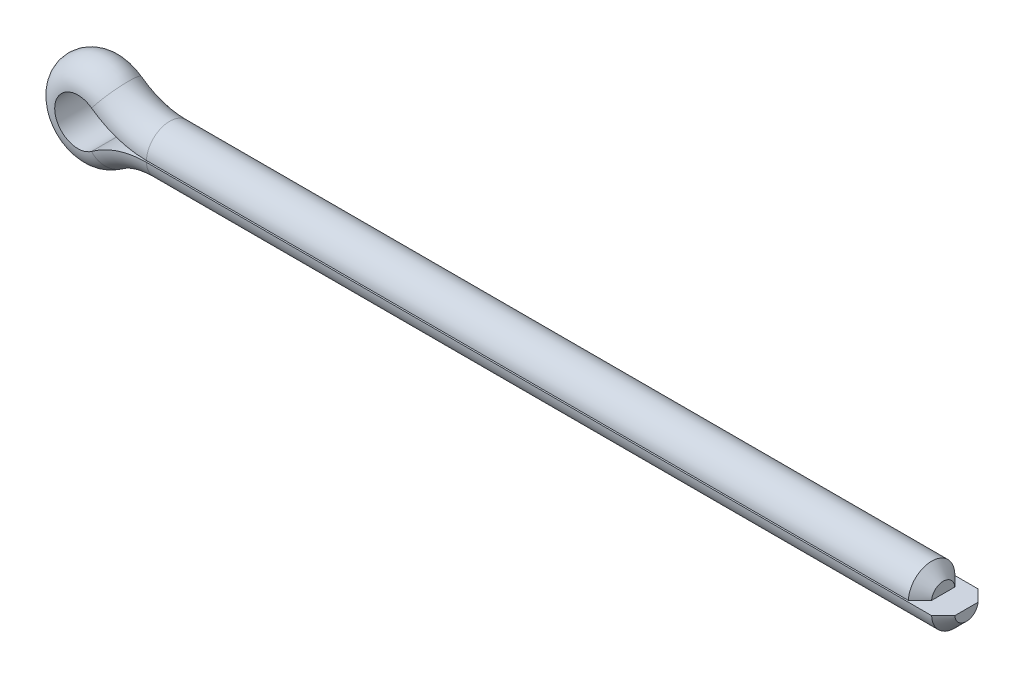
SolidWorks part; units mm, degrees
material "AISI 1020 Steel, Cold Rolled"
ref_plane "Front" through (0, 0, 0) normal (0, 0, 1) x (1, 0, 0)
ref_plane "Top" through (0, 0, 0) normal (0, 1, 0) x (1, 0, 0)
ref_plane "Right" through (0, 0, 0) normal (1, 0, 0) x (0, 0, -1)
sketch "Sketch1" plane through (0, 0, 0) normal (0, 0, 1) x (1, 0, 0)
  line L0 (-27.6517, 0) -> (0.762, 0) construction
  line L1 (-25.4, -0.0254) -> (0.762, -0.0254)
  line L2 (-26.8902, 0.0254) -> (0.762, 0.0254) construction
  line L3 (-25.4, 0.0254) -> (0, 0.0254)
  line L4 (-11.4985, 0.0254) -> (0.762, 0.0254) construction
  line L5 (-11.4985, -0.0254) -> (0.762, -0.0254) construction
  line L6 (-27.6517, 0.762) -> (-27.6517, 0) construction
  line L7 (-27.6517, 0.762) -> (-27.6517, 1.524) construction
  line L8 (-11.4985, 0) -> (0.762, 0) construction
  line L9 (0, 0.0254) -> (0, 0) construction
  line L10 (-27.6517, 0) -> (-27.6517, -1.524) construction
  line L11 (-25.4, 0.7366) -> (-25.4, -0.7874) construction
  arc A1 (-27.2014, 0.6147) -> (-27.2014, -0.6147) centre (-27.6517, 0) ccw
  arc A2 (-25.4, -0.0254) -> (-27.2014, -0.6147) centre (-25.4, -3.0734) ccw
  arc A3 (-27.2014, 0.6147) -> (-25.4, 0.0254) centre (-25.4, 3.0734) ccw
  circle A4 centre (-27.6517, 0) radius 1.524 construction
  point P15 (0, 0.0254)
  dimension "D6" = 3.048
  dimension "Head Diameter" = 3.048
  dimension "ExtendedProngLength" = 0.762
  dimension "Length" = 25.4
  dimension "Diameter" = 1.524
  dimension "D1" = 0.762
  dimension "D4" = 0.0254
  dimension "D5" = 0.0254
sketch "Sketch2" plane through (0, 0, 0) normal (1, 0, 0) x (0, 0, -1)
  line L0 (-0.7616, 0.0254) -> (0.7616, 0.0254)
  line L1 (0, 0.762) -> (0, -0.762) construction
  circle A1 centre (0, 0) radius 0.762 construction
  arc A2 (-0.7616, 0.0254) -> (0.7616, 0.0254) centre (0, 0) cw
  point P5 (0, 0)
  dimension "D1" = 0.762
sketch "Sketch3" plane through (0, 0, 0) normal (0, 0, 1) x (1, 0, 0)
  line L0 (-25.4, -0.0254) -> (0.762, -0.0254) construction
  line L1 (-25.4, 0.0254) -> (0, 0.0254) construction
  line L2 (-25.4, -0.0254) -> (0.762, -0.0254)
  line L3 (-25.4, 0.0254) -> (0, 0.0254)
  arc A0 (-25.4, -0.0254) -> (-27.2014, -0.6147) centre (-25.4, -3.0734) ccw construction
  arc A1 (-27.2014, 0.6147) -> (-25.4, 0.0254) centre (-25.4, 3.0734) ccw construction
  arc A2 (-27.2014, 0.6147) -> (-27.2014, -0.6147) centre (-27.6517, 0) ccw construction
  arc A3 (-25.4, -0.0254) -> (-27.2014, -0.6147) centre (-25.4, -3.0734) ccw
  arc A4 (-27.2014, 0.6147) -> (-25.4, 0.0254) centre (-25.4, 3.0734) ccw
  arc A5 (-27.2014, 0.6147) -> (-27.2014, -0.6147) centre (-27.6517, 0) ccw
sketch "Sketch4" plane through (0, 0, 0) normal (1, 0, 0) x (0, 0, -1)
  line L0 (-0.7616, 0.0254) -> (0.7616, 0.0254) construction
  line L1 (-0.7616, 0.0254) -> (0.7616, 0.0254)
  arc A2 (0.7616, 0.0254) -> (-0.7616, 0.0254) centre (0, 0) ccw construction
  arc A3 (0.7616, 0.0254) -> (-0.7616, 0.0254) centre (0, 0) ccw
sweep "Sweep1" add profiles "Sketch4" path "Sketch3"
chamfer "Chamfer1" distance 0.381 angle 45 2 edges at (0.762, -0.762, 0) (0, 0.762, 0)
equation "\"D6@Sketch1\"=\"Head Diameter@Sketch1\""
equation "\"D1@Sketch2\"=\"Diameter@Sketch1\"/2"
equation "\"ExtendedProngLength@Sketch1\" = \"Length@Sketch1\"*.09"
equation "\"D1@Chamfer1\"=\"Diameter@Sketch1\"/4"
equation "\"D1@Sketch1\"=\"Diameter@Sketch1\"/2"
